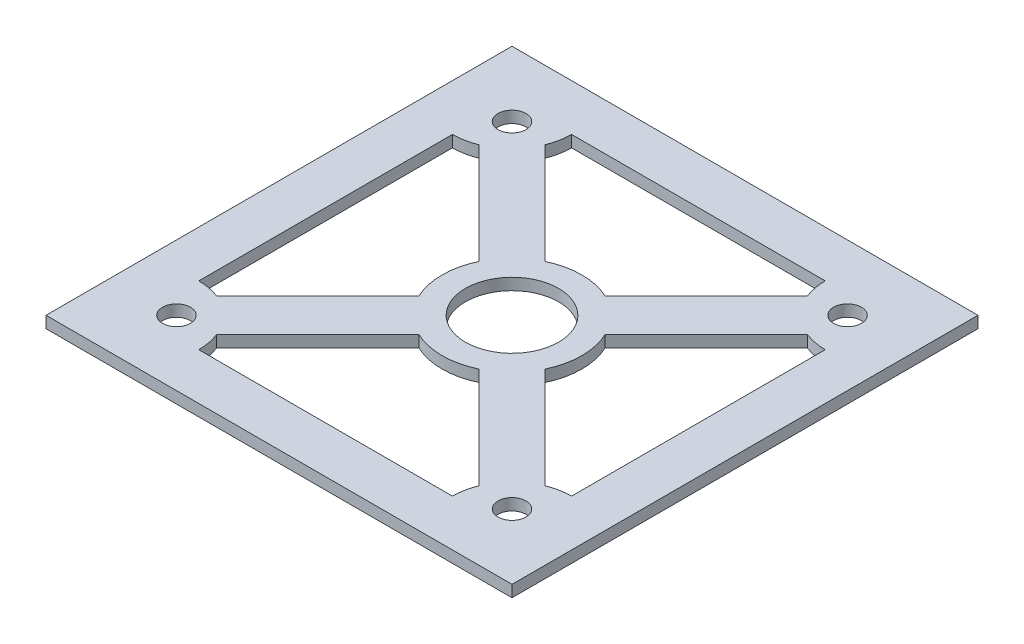
SolidWorks part; units mm, degrees
ref_plane "Front Plane" through (0, 0, 0) normal (0, 0, 1) x (1, 0, 0)
ref_plane "Top Plane" through (0, 0, 0) normal (0, 1, 0) x (1, 0, 0)
ref_plane "Right Plane" through (0, 0, 0) normal (1, 0, 0) x (0, 0, -1)
sketch "Sketch1" plane through (0, 0, 0) normal (0, 1, 0) x (1, 0, 0)
  line L1 (-50, -50) -> (50, -50)
  line L2 (-50, -50) -> (-50, 50)
  line L3 (-50, 50) -> (50, 50)
  line L4 (50, -50) -> (50, 50)
  line L5 (-50, -50) -> (50, 50) construction
  line L6 (-50, 50) -> (50, -50) construction
  point P0 (0, 0)
  dimension "D1" = 100
extrude "Boss-Extrude1" add sketch "Sketch1" along normal blind 2.5
sketch "Sketch4" plane through (0, 2.5, 0) normal (0, 1, 0) x (1, 0, 0)
sketch "Sketch5" plane through (0, 2.5, 0) normal (0, 1, 0) x (1, 0, 0)
  line L1 (-40, -40) -> (40, -40)
  line L2 (-40, -40) -> (-40, 40)
  line L3 (-40, 40) -> (40, 40)
  line L4 (40, -40) -> (40, 40)
  line L5 (-40, -40) -> (40, 40) construction
  line L6 (-40, 40) -> (40, -40) construction
  line L7 (50, -50) -> (50, 50) construction
  line L8 (-50, -50) -> (50, -50) construction
  point P0 (0, 0)
  dimension "D1" = 10
  dimension "D2" = 10
extrude "Cut-Extrude2" cut sketch "Sketch5" against normal blind 4
sketch "Sketch6" plane through (0, 2.5, 0) normal (0, 1, 0) x (1, 0, 0)
  circle A0 centre (0, 0) radius 15
  dimension "D1" = 30
extrude "Boss-Extrude3" add sketch "Sketch6" against normal blind 2.5 separate body
sketch "Sketch7" plane through (0, 2.5, 0) normal (0, 1, 0) x (1, 0, 0)
  line L1 (-2.5, -2.5) -> (2.5, -2.5)
  line L2 (-2.5, -2.5) -> (-2.5, 2.5)
  line L3 (-2.5, 2.5) -> (2.5, 2.5)
  line L4 (2.5, -2.5) -> (2.5, 2.5)
  line L5 (-2.5, -2.5) -> (2.5, 2.5) construction
  line L6 (-2.5, 2.5) -> (2.5, -2.5) construction
  point P0 (0, 0)
  dimension "D1" = 5
  dimension "D2" = 5
extrude "Cut-Extrude3" cut sketch "Sketch7" against normal blind 2.5
sketch "Sketch8" plane through (0, 2.5, 0) normal (0, 1, 0) x (1, 0, 0)
  line L0 (40, -40) -> (40, 40) construction
  line L1 (40, 40) -> (-40, 40) construction
  line L2 (0, -54.2426) -> (0, 54.2426)
  line L3 (27.2201, 40) -> (40, 40)
  line L4 (40, 40) -> (40, 27.2201)
  line L5 (-63.2717, 0) -> (63.2717, 0)
  arc A0 (40, 27.2201) -> (27.2201, 40) centre (40, 40) cw
  arc A1 (-40, 27.2201) -> (-27.2201, 40) centre (-40, 40) ccw
  arc A2 (40, -27.2201) -> (27.2201, -40) centre (40, -40) ccw
  arc A3 (-40, -27.2201) -> (-27.2201, -40) centre (-40, -40) cw
  point P13 (0, 0)
  point P15 (0, 0)
  line M3 (-40, 40) -> (40, 40)
  line M4 (40, 40) -> (40, -40)
  line M5 (40, -40) -> (-40, -40)
  line M6 (-40, -40) -> (-40, 40)
extrude "Boss-Extrude4" add sketch "Sketch8" against normal blind 2.5 contours A3 M6 M5 | A1 M6 M3 | A0 M4 M3 | A2 M4 M5
sketch "Sketch9" plane through (0, 2.5, 0) normal (0, 1, 0) x (1, 0, 0)
  line L0 (2.5, -2.5) -> (38.0042, -38.0042)
  line L2 (-7.75, -7.75) -> (-38.0042, -38.0042)
  line L4 (7.75, 7.75) -> (38.0042, 38.0042)
  line L5 (-7.75, 7.75) -> (-38.0042, 38.0042)
  point P17 (0, 0)
  point P22 (0, 0)
extrude "Extrude-Thin2" add sketch "Sketch9" against normal blind 2.5 thin thin type mid plane wall 10
sketch "Sketch10" plane through (0, 2.5, 0) normal (0, 1, 0) x (1, 0, 0)
  line L0 (50, 50) -> (-50, 50) construction
  line L1 (50, -50) -> (50, 50) construction
  line L2 (-81.3718, 0) -> (93.495, 0) construction
  line L3 (0, 82.8678) -> (0, -87.0228) construction
  circle A0 centre (36, 36) radius 3
  circle A1 centre (-36, 36) radius 3
  circle A2 centre (36, -36) radius 3
  circle A3 centre (-36, -36) radius 3
  dimension "D1" = 6
  dimension "D2" = 14
  dimension "D3" = 14
extrude "Cut-Extrude5" cut sketch "Sketch10" against normal blind 2.5
sketch "Sketch11" plane through (0, 2.5, 0) normal (0, 1, 0) x (1, 0, 0)
sketch "Sketch12" plane through (0, 2.5, 0) normal (0, 1, 0) x (1, 0, 0)
  circle A0 centre (0, 0) radius 10
  dimension "D1" = 20
extrude "Cut-Extrude7" cut sketch "Sketch12" against normal blind 10 contours A0
